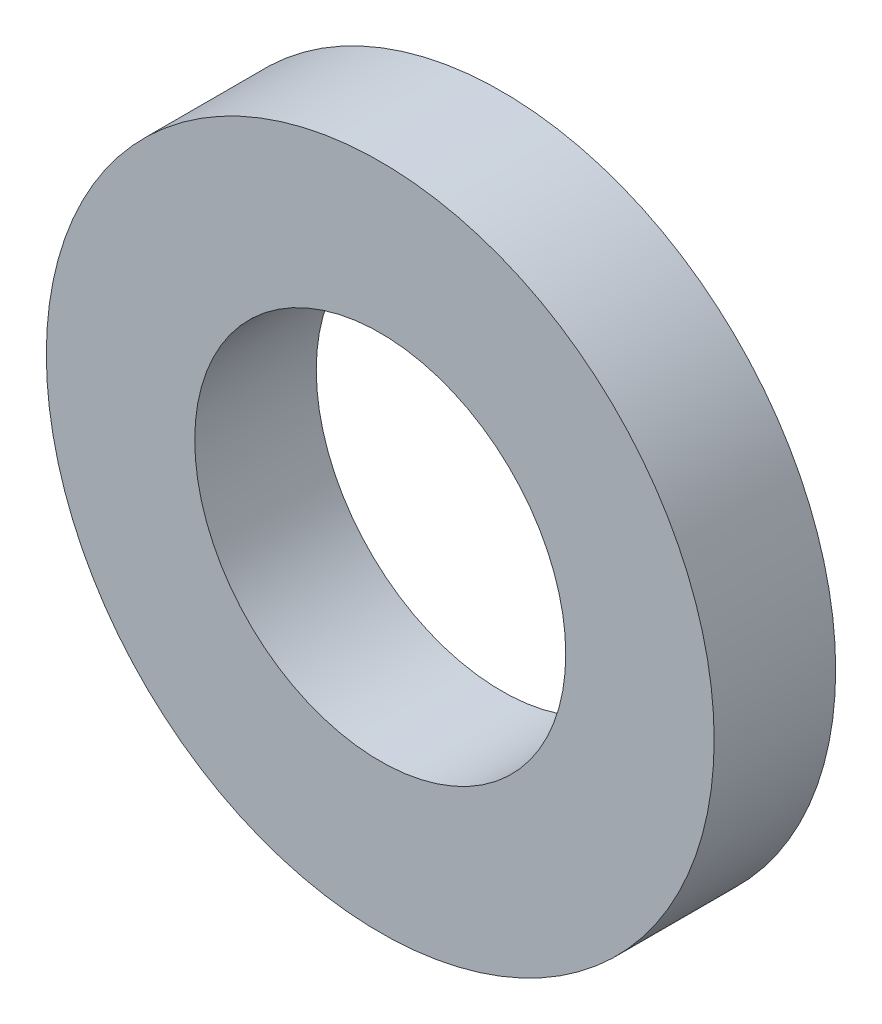
SolidWorks part; units mm, degrees
material "ABS"
ref_plane "Front Plane" through (0, 0, 0) normal (0, 0, 1) x (1, 0, 0)
ref_plane "Top Plane" through (0, 0, 0) normal (0, 1, 0) x (1, 0, 0)
ref_plane "Right Plane" through (0, 0, 0) normal (1, 0, 0) x (0, 0, -1)
sketch "Sketch1" plane through (0, 0, 0) normal (0, 0, 1) x (1, 0, 0)
  circle A0 centre (0, 0) radius 2.5
  circle A1 centre (0, 0) radius 4.5
  dimension "D1" = 5
  dimension "D2" = 9
extrude "Boss-Extrude1" add sketch "Sketch1" along normal mid plane 1.6375
